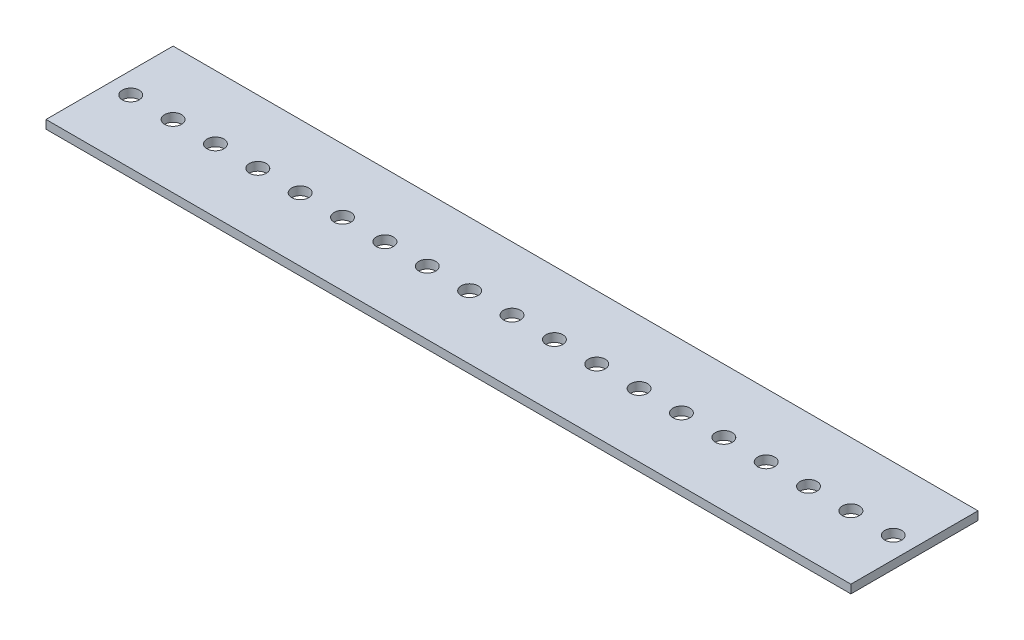
SolidWorks part; units mm, degrees
ref_plane "Front Plane" through (0, 0, 0) normal (0, 0, 1) x (1, 0, 0)
ref_plane "Top Plane" through (0, 0, 0) normal (0, 1, 0) x (1, 0, 0)
ref_plane "Right Plane" through (0, 0, 0) normal (1, 0, 0) x (0, 0, -1)
sketch "Sketch1" plane through (0, 0, 0) normal (0, 1, 0) x (1, 0, 0)
  line L1 (-120.65, -19.05) -> (120.65, -19.05)
  line L2 (-120.65, -19.05) -> (-120.65, 19.05)
  line L3 (-120.65, 19.05) -> (120.65, 19.05)
  line L4 (120.65, -19.05) -> (120.65, 19.05)
  line L5 (-120.65, -19.05) -> (120.65, 19.05) construction
  line L6 (-120.65, 19.05) -> (120.65, -19.05) construction
  point P0 (0, 0)
  dimension "D1" = 38.1
  dimension "D2" = 241.3
extrude "Boss-Extrude1" add sketch "Sketch1" along normal blind 2.54
sketch "Sketch2" plane through (0, 2.54, 0) normal (0, 1, 0) x (1, 0, 0)
  circle A0 centre (-114.3, 0) radius 2.54
  point P2 (-111.6981, 0)
  point P3 (0, 0)
extrude "Cut-Extrude1" cut sketch "Sketch2" against normal blind 2.54
pattern_linear "LPattern1" count 19 spacing 12.7 along (1, 0, 0) of "Cut-Extrude1"
sketch "Sketch5" plane through (0, 2.54, 0) normal (0, 1, 0) x (1, 0, 0)
  line L0 (-120.65, 19.05) -> (120.65, 19.05) construction
  line L1 (-95.25, -19.05) -> (95.25, -19.05)
  line L2 (-95.25, -19.05) -> (-95.25, 19.05)
  line L3 (-95.25, 19.05) -> (95.25, 19.05)
  line L4 (95.25, -19.05) -> (95.25, 19.05)
  line L5 (-95.25, -19.05) -> (95.25, 19.05) construction
  line L6 (-95.25, 19.05) -> (95.25, -19.05) construction
  point P0 (0, 0)
  dimension "D1" = 190.5
  dimension "D2" = 38.1
